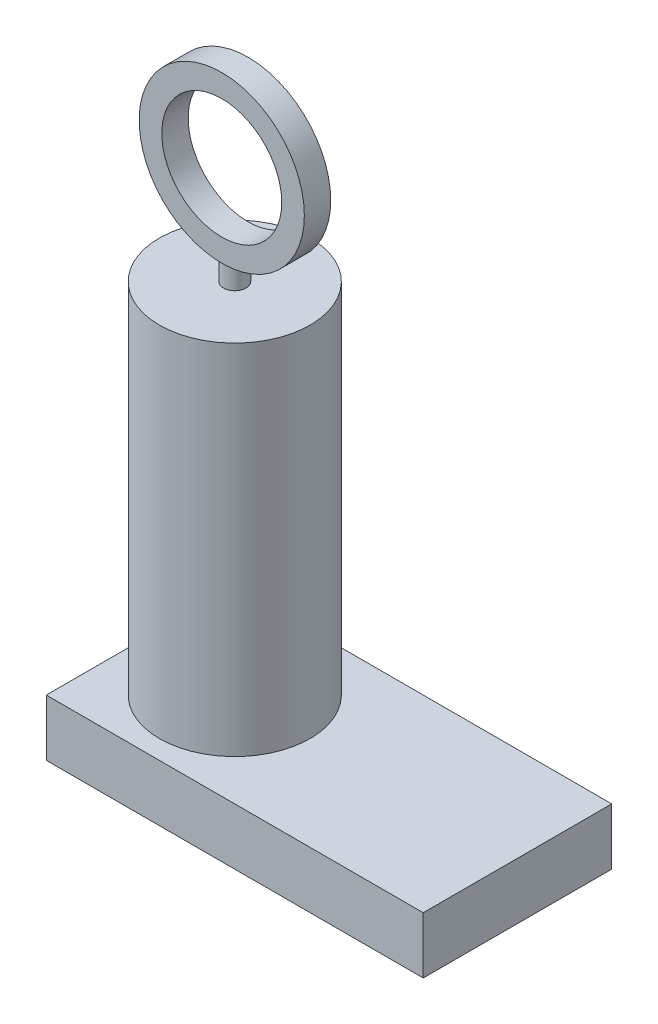
SolidWorks part; units mm, degrees
ref_plane "Front Plane" through (0, 0, 0) normal (0, 0, 1) x (1, 0, 0)
ref_plane "Top Plane" through (0, 0, 0) normal (0, 1, 0) x (1, 0, 0)
ref_plane "Right Plane" through (0, 0, 0) normal (1, 0, 0) x (0, 0, -1)
sketch "Sketch1" plane through (0, 0, 0) normal (0, 1, 0) x (1, 0, 0)
  circle A0 centre (0, 0) radius 40
  dimension "D1" = 80
extrude "Boss-Extrude1" add sketch "Sketch1" along normal blind 190
sketch "Sketch3" plane through (0, 0, 0) normal (0, -1, 0) x (1, 0, 0)
  line L0 (0, 0) -> (155.8534, 0) construction
  line L1 (-50, 50) -> (150, 50)
  line L2 (-50, 50) -> (-50, -50)
  line L3 (-50, -50) -> (150, -50)
  line L4 (150, 50) -> (150, -50)
  dimension "D1" = 50
  dimension "D2" = 200
  dimension "100" = 100
extrude "Boss-Extrude3" add sketch "Sketch3" along normal blind 30
sketch "Sketch4" plane through (0, 190, 0) normal (0, 1, 0) x (1, 0, 0)
  circle A0 centre (0, 0) radius 6
  dimension "D1" = 12
extrude "Boss-Extrude4" add sketch "Sketch4" along normal blind 20
sketch "Sketch5" plane through (0, 0, 0) normal (1, 0, 0) x (0, 0, -1)
  line L1 (-6.9006, 201.8771) -> (7.0994, 201.8771)
  line L2 (-6.9006, 201.8771) -> (-6.9006, 213.8771)
  line L3 (-6.9006, 213.8771) -> (7.0994, 213.8771)
  line L4 (7.0994, 201.8771) -> (7.0994, 213.8771)
  line L5 (-6, 245.699) -> (7.4149, 245.699) construction
  line L6 (0.0994, 213.8771) -> (0.0994, 203.938) construction
  line L7 (6, 210) -> (-6, 210) construction
  dimension "D1" = 12
  dimension "D2" = 14
revolve "Revolve1" add sketch "Sketch5" angle 360 about L5
